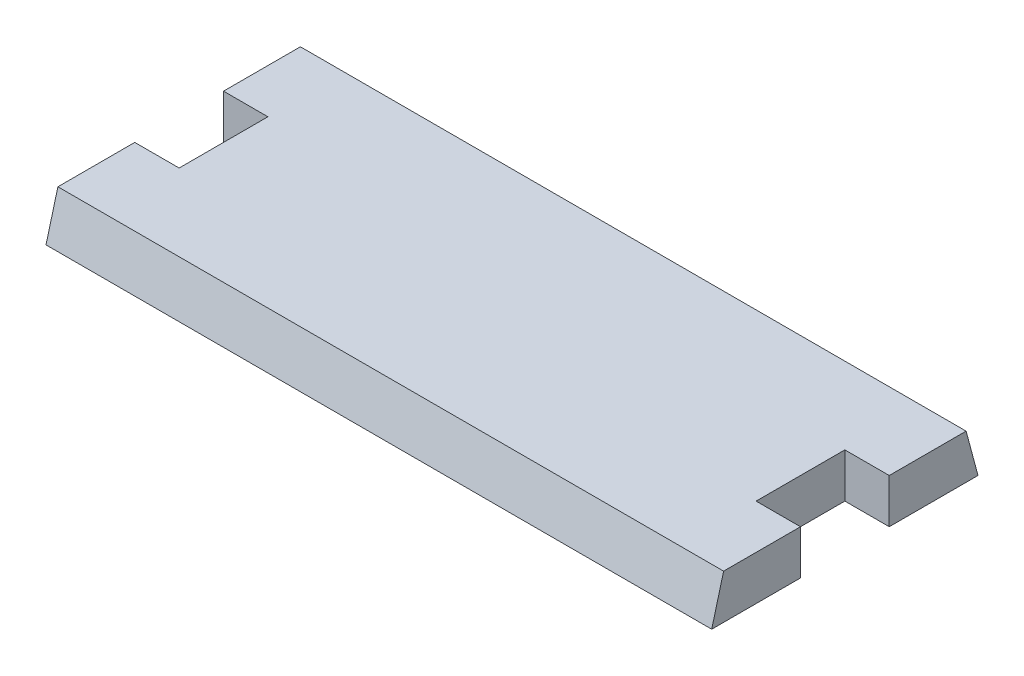
SolidWorks part; units mm, degrees
ref_plane "Front Plane" through (0, 0, 0) normal (0, 0, 1) x (1, 0, 0)
ref_plane "Top Plane" through (0, 0, 0) normal (0, 1, 0) x (1, 0, 0)
ref_plane "Right Plane" through (0, 0, 0) normal (1, 0, 0) x (0, 0, -1)
sketch "Sketch2" plane through (0, 0, 0) normal (0, 1, 0) x (1, 0, 0)
  line L0 (-3810, -1016) -> (-3810, -1524)
  line L1 (0, 0) -> (-3810, 0)
  line L2 (0, 0) -> (0, -508)
  line L3 (0, -1524) -> (-3810, -1524)
  line L4 (-3810, 0) -> (-3810, -508)
  line L5 (0, -508) -> (-254, -508)
  line L7 (0, -1016) -> (-254, -1016)
  line L8 (-254, -508) -> (-254, -1016)
  line L9 (-3810, -508) -> (-3556, -508)
  line L11 (-3810, -1016) -> (-3556, -1016)
  line L12 (-3556, -508) -> (-3556, -1016)
  line L13 (0, -1016) -> (0, -1524)
  dimension "D1" = 3810
  dimension "D2" = 1524
  dimension "D3" = 508
  dimension "D4" = 508
  dimension "D5" = 254
  dimension "D6" = 254
  dimension "D7" = 508
  dimension "D8" = 508
extrude "Boss-Extrude1" add sketch "Sketch2" along normal blind 254
draft "Draft1" type of draft neutral plane draft angle 15 faces to draft 2 face at (-1905, 127, 0) face at (-1905, 127, 1524) neutral plane through (0, 0, 0) neutral plane normal (0, -1, 0) reverse direction yes parameters "D1"=15
